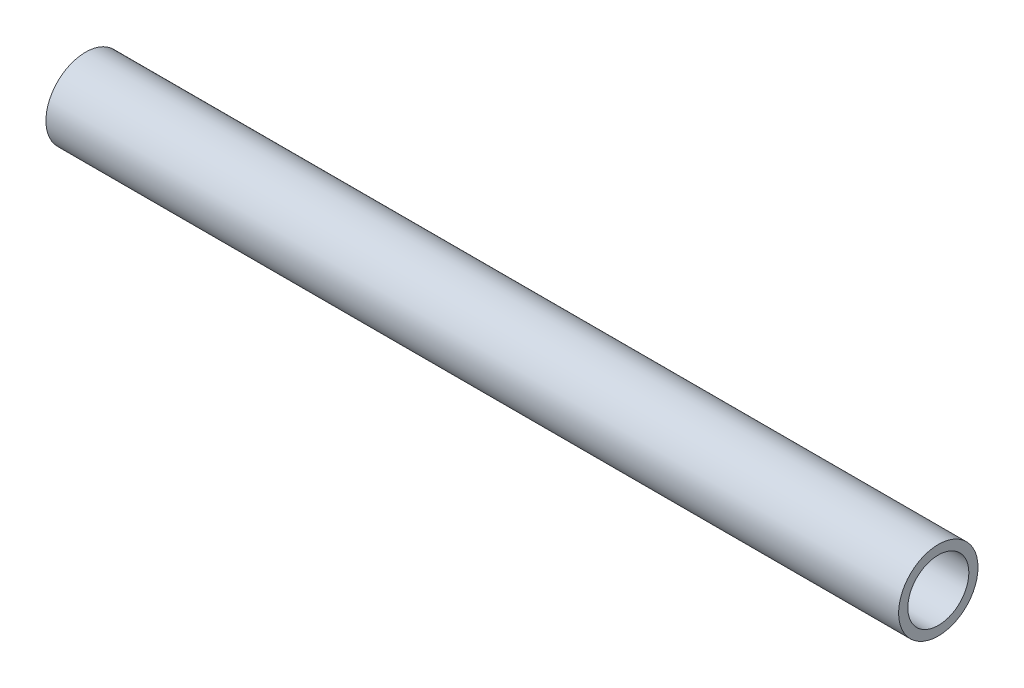
SolidWorks part; units mm, degrees
material "Alloy Steel"
ref_plane "Front Plane" through (0, 0, 0) normal (0, 0, 1) x (1, 0, 0)
ref_plane "Top Plane" through (0, 0, 0) normal (0, 1, 0) x (1, 0, 0)
ref_plane "Right Plane" through (0, 0, 0) normal (1, 0, 0) x (0, 0, -1)
sketch "Sketch1" plane through (0, 0, 0) normal (1, 0, 0) x (0, 0, -1)
  circle A0 centre (0, 0) radius 5
  circle A1 centre (0, 0) radius 6.5
  dimension "D1" = 13
  dimension "D2" = 10
extrude "Boss-Extrude1" add sketch "Sketch1" along normal blind 139.7
